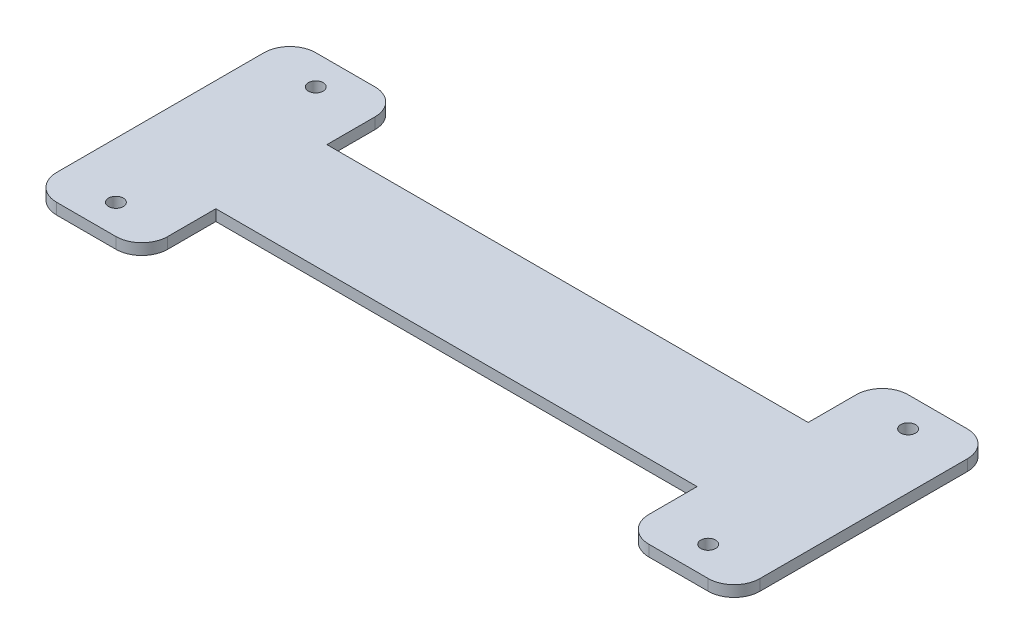
SolidWorks part; units mm, degrees
material "Caoba"
ref_plane "Alzado" through (0, 0, 0) normal (0, 0, 1) x (1, 0, 0)
ref_plane "Planta" through (0, 0, 0) normal (0, 1, 0) x (1, 0, 0)
ref_plane "Vista lateral" through (0, 0, 0) normal (1, 0, 0) x (0, 0, -1)
sketch "Croquis1" plane through (0, 0, 0) normal (0, 1, 0) x (1, 0, 0)
  line L1 (0, 0) -> (190, 0)
  line L2 (0, 0) -> (0, -70)
  line L3 (0, -70) -> (190, -70)
  line L4 (190, 0) -> (190, -70)
  dimension "D1" = 190
  dimension "D2" = 70
extrude "Saliente-Extruir1" add sketch "Croquis1" along normal blind 3
sketch "Croquis2" plane through (0, 3, 0) normal (0, 1, 0) x (1, 0, 0)
  line L0 (95, 0) -> (95, -70) construction
  line L1 (190, 0) -> (0, 0) construction
  line L2 (0, -70) -> (190, -70) construction
  line L3 (0, -35) -> (190, -35) construction
  line L4 (0, 0) -> (0, -70) construction
  line L5 (190, -70) -> (190, 0) construction
  line L6 (30, 0) -> (160, 0)
  line L7 (30, -50) -> (160, -50)
  line L8 (30, -50) -> (30, -70)
  line L9 (30, -70) -> (160, -70)
  line L10 (160, -50) -> (160, -70)
  line L11 (160, -20) -> (160, 0)
  line L12 (30, -20) -> (160, -20)
  line L13 (30, -20) -> (30, 0)
  circle A0 centre (15, -8) radius 2
  circle A1 centre (175, -8) radius 2
  circle A2 centre (175, -62) radius 2
  circle A3 centre (15, -62) radius 2
  dimension "D1" = 54
  dimension "D2" = 54
  dimension "D3" = 4
  dimension "D4" = 4
  dimension "D5" = 4
  dimension "D6" = 4
  dimension "D7" = 160
  dimension "D8" = 160
  dimension "D9" = 80
  dimension "D10" = 27
  dimension "D11" = 80
  dimension "D12" = 27
  dimension "D13" = 30
  dimension "D14" = 30
  dimension "D15" = 20
extrude "Cortar-Extruir1" cut sketch "Croquis2" against normal blind 3
fillet "Redondeo1" radius 7 8 edges at (190, 1.5, 0) (160, 1.5, 0) (160, 1.5, 70) (190, 1.5, 70) (30, 1.5, 70) (0, 1.5, 70) (0, 1.5, 0) (30, 1.5, 0)
